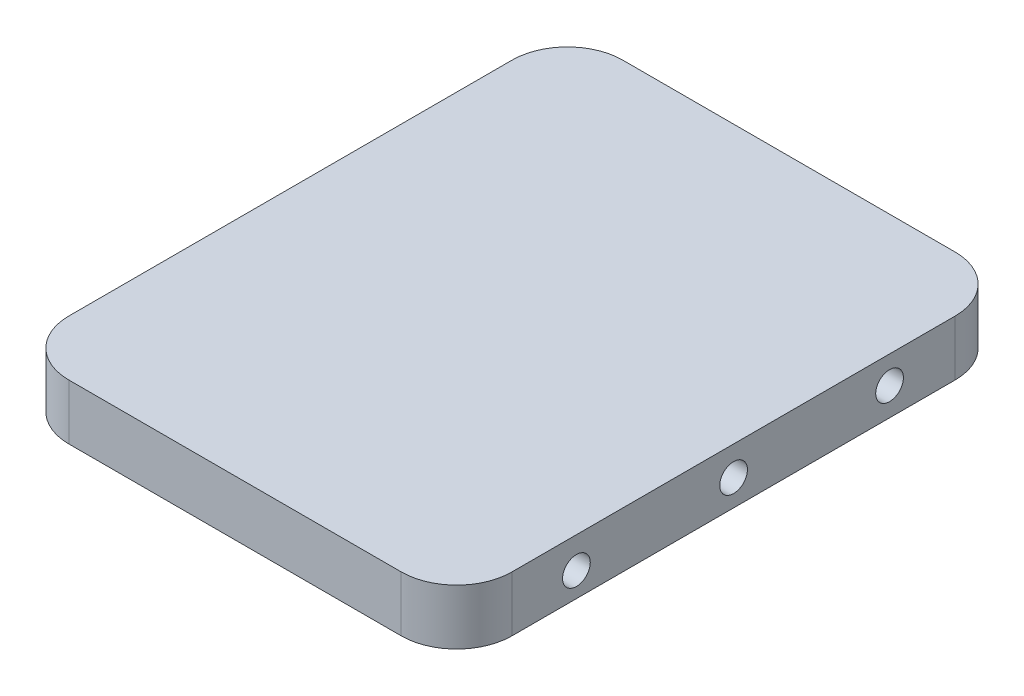
SolidWorks part; units mm, degrees
ref_plane "Front Plane" through (0, 0, 0) normal (0, 0, 1) x (1, 0, 0)
ref_plane "Top Plane" through (0, 0, 0) normal (0, 1, 0) x (1, 0, 0)
ref_plane "Right Plane" through (0, 0, 0) normal (1, 0, 0) x (0, 0, -1)
sketch "Sketch1" plane through (0, 0, 0) normal (0, 1, 0) x (1, 0, 0)
  line L0 (-70.5463, 0) -> (65.4732, 0) construction
  line L2 (-30, 50) -> (30, 50)
  line L3 (-40, 40) -> (-40, -40)
  line L4 (-30, -50) -> (30, -50)
  line L5 (40, 40) -> (40, -40)
  line L6 (-40, 50) -> (40, -50) construction
  line L7 (-40, -50) -> (40, 50) construction
  arc A0 (-40, -40) -> (-30, -50) centre (-30, -40) ccw
  arc A1 (30, -50) -> (40, -40) centre (30, -40) ccw
  arc A2 (30, 50) -> (40, 40) centre (30, 40) cw
  arc A3 (-30, 50) -> (-40, 40) centre (-30, 40) ccw
  point P3 (0, 0)
  dimension "D3" = 10
  dimension "D1" = 80
  dimension "D2" = 100
extrude "Boss-Extrude1" add sketch "Sketch1" along normal blind 10
sketch "Sketch2" plane through (40, 0, 0) normal (1, 0, 0) x (0, 0, -1)
  line L6 (-74.0377, 4.7438) -> (54.1623, 4.7438) construction
  line L8 (-40, 0) -> (40, 0) construction
  circle A0 centre (0, 4.7438) radius 2.5
  circle A1 centre (30.8768, 4.7438) radius 2.5
  circle A2 centre (-30.3323, 4.7438) radius 2.5
  point P6 (0, 0)
  dimension "D1" = 4.7438
extrude "Cut-Extrude1" cut sketch "Sketch2" against normal through all contours A0
sketch "Sketch4" plane through (40, 0, 0) normal (1, 0, 0) x (0, 0, -1)
  circle A0 centre (-28.3718, 4.401) radius 2.5
extrude "Cut-Extrude2" cut sketch "Sketch4" against normal through all
sketch "Sketch5" plane through (40, 0, 0) normal (1, 0, 0) x (0, 0, -1)
  circle A0 centre (28.154, 5.042) radius 2.5
extrude "Cut-Extrude3" cut sketch "Sketch5" against normal through all
